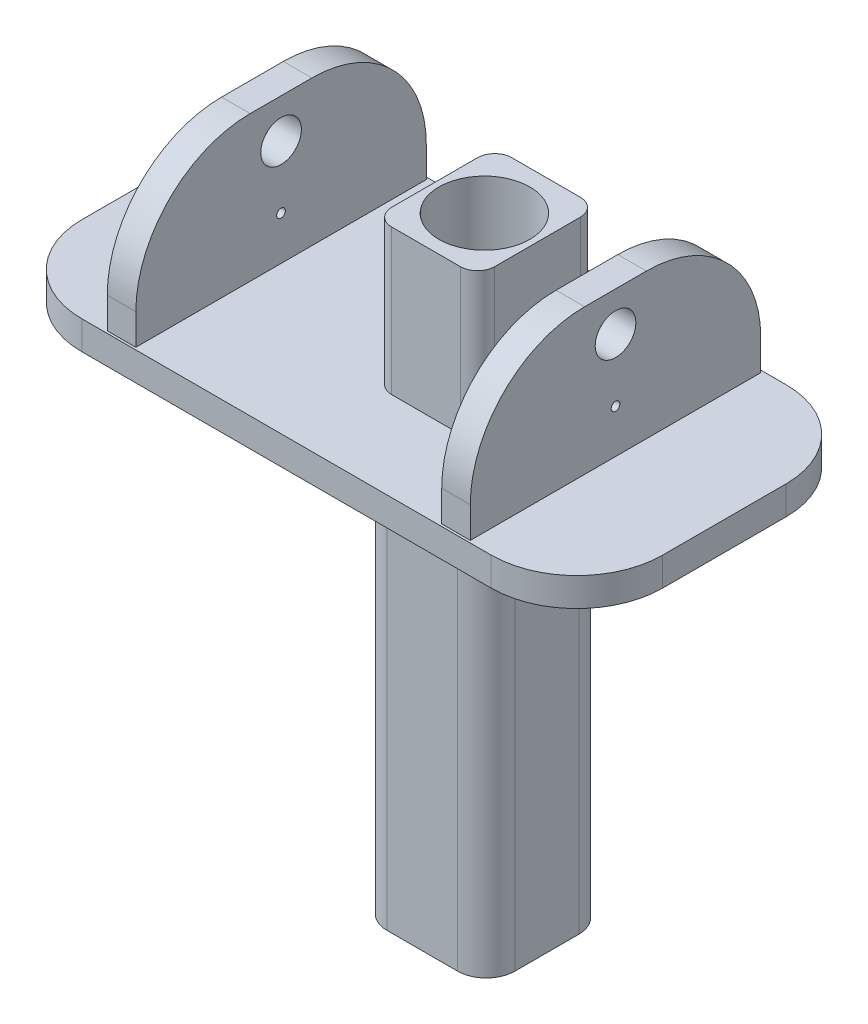
SolidWorks part; units mm, degrees
ref_plane "Front Plane" through (0, 0, 0) normal (0, 0, 1) x (1, 0, 0)
ref_plane "Top Plane" through (0, 0, 0) normal (0, 1, 0) x (1, 0, 0)
ref_plane "Right Plane" through (0, 0, 0) normal (1, 0, 0) x (0, 0, -1)
sketch "Sketch2" plane through (0, 0, 0) normal (0, 1, 0) x (1, 0, 0)
  line L1 (0, 0) -> (101.6, 0)
  line L2 (0, 0) -> (0, -101.6)
  line L3 (0, -101.6) -> (101.6, -101.6)
  line L4 (101.6, 0) -> (101.6, -101.6)
  dimension "D1" = 101.6
  dimension "D2" = 101.6
extrude "Boss-Extrude2" add sketch "Sketch2" along normal blind 5
sketch "Sketch3" plane through (0, 5, 0) normal (0, 1, 0) x (1, 0, 0)
  line L0 (0, 0) -> (0, -101.6) construction
  line L1 (19.05, -25.4) -> (24.05, -25.4)
  line L2 (19.05, -25.4) -> (19.05, -76.2)
  line L3 (19.05, -76.2) -> (24.05, -76.2)
  line L4 (24.05, -25.4) -> (24.05, -76.2)
  line L5 (0, -101.6) -> (101.6, -101.6) construction
  dimension "D1" = 5
  dimension "D2" = 19.05
  dimension "D3" = 50.8
  dimension "D4" = 25.4
extrude "Boss-Extrude3" add sketch "Sketch3" along normal blind 25.4
sketch "Sketch4" plane through (0, 5, 0) normal (0, 1, 0) x (1, 0, 0)
  line L0 (101.6, -101.6) -> (101.6, 0) construction
  line L1 (77.55, -25.4) -> (82.55, -25.4)
  line L2 (77.55, -25.4) -> (77.55, -76.2)
  line L3 (77.55, -76.2) -> (82.55, -76.2)
  line L4 (82.55, -25.4) -> (82.55, -76.2)
  line L5 (0, -101.6) -> (101.6, -101.6) construction
  dimension "D1" = 5
  dimension "D2" = 19.05
  dimension "D3" = 50.8
  dimension "D4" = 25.4
extrude "Boss-Extrude4" add sketch "Sketch4" along normal blind 25.4
sketch "Sketch8" plane through (19.05, 0, 0) normal (-1, 0, 0) x (0, 0, 1)
  line L0 (76.2, 30.4) -> (76.2, 5) construction
  line L1 (25.4, 5) -> (76.2, 5) construction
  circle A0 centre (50.8, 23.542) radius 3.556
  dimension "D1" = 25.4
  dimension "D2" = 18.542
extrude "Cut-Extrude1" cut sketch "Sketch8" against normal through all
sketch "Sketch9" plane through (82.55, 0, 0) normal (1, 0, 0) x (0, 0, -1)
  line L0 (-76.2, 30.4) -> (-76.2, 5) construction
  line L1 (-76.2, 5) -> (-25.4, 5) construction
  circle A0 centre (-50.8, 12.62) radius 0.762
  dimension "D1" = 25.4
  dimension "D2" = 7.62
extrude "Cut-Extrude2" cut sketch "Sketch9" against normal up to next
sketch "Sketch11" plane through (0, 5, 0) normal (0, 1, 0) x (1, 0, 0)
  line L0 (24.05, -76.2) -> (24.05, -25.4) construction
  line L1 (0, -101.6) -> (101.6, -101.6) construction
  circle A0 centre (59.61, -50.8) radius 7.9502
  dimension "D1" = 35.56
  dimension "D2" = 50.8
extrude "Cut-Extrude3" cut sketch "Sketch11" against normal through all
sketch "Sketch18" plane through (19.05, 0, 0) normal (-1, 0, 0) x (0, 0, 1)
  line L0 (0, 5) -> (101.6, 5) construction
  line L1 (25.4, 30.4) -> (25.4, 5) construction
  circle A0 centre (50.8, 12.62) radius 0.762
  dimension "D1" = 7.62
  dimension "D2" = 25.4
extrude "Cut-Extrude5" cut sketch "Sketch18" against normal up to next
sketch "Sketch19" plane through (0, 0, 0) normal (0, -1, 0) x (1, 0, 0)
  line L1 (48.1494, 61.3607) -> (70.4999, 61.3607)
  line L2 (48.1494, 61.3607) -> (48.1494, 40.1623)
  line L3 (48.1494, 40.1623) -> (70.4999, 40.1623)
  line L4 (70.4999, 61.3607) -> (70.4999, 40.1623)
extrude "Boss-Extrude5" add sketch "Sketch19" along normal blind 76.2
sketch "Sketch22" plane through (0, 0, 0) normal (0, 1, 0) x (1, 0, 0)
  circle A0 centre (59.61, -50.8) radius 7.94
extrude "Cut-Extrude7" cut sketch "Sketch22" against normal blind 72.2
sketch "Sketch23" plane through (0, -76.2, 0) normal (0, -1, 0) x (1, 0, 0)
  circle A0 centre (59.61, 50.8) radius 4.95
extrude "Cut-Extrude8" cut sketch "Sketch23" against normal through all
sketch "Sketch24" plane through (0, 5, 0) normal (0, 1, 0) x (1, 0, 0)
  line L0 (101.6, -101.6) -> (101.6, 0) construction
  line L1 (0, 0) -> (101.6, 0)
  line L2 (0, 0) -> (0, -25)
  line L3 (0, -25) -> (101.6, -25)
  line L4 (101.6, 0) -> (101.6, -25)
extrude "Cut-Extrude9" cut sketch "Sketch24" against normal through all
sketch "Sketch25" plane through (0, 5, 0) normal (0, 1, 0) x (1, 0, 0)
  line L0 (101.6, -101.6) -> (101.6, -25) construction
  line L1 (0, -101.6) -> (101.6, -101.6)
  line L2 (0, -101.6) -> (0, -76.6)
  line L3 (0, -76.6) -> (101.6, -76.6)
  line L4 (101.6, -101.6) -> (101.6, -76.6)
extrude "Cut-Extrude10" cut sketch "Sketch25" against normal through all
fillet "Fillet1" radius 20 1 edges at (21.55, 30.4, 76.2)
fillet "Fillet2" radius 20 1 edges at (21.55, 30.4, 25.4)
fillet "Fillet3" radius 20 1 edges at (80.05, 30.4, 25.4)
fillet "Fillet4" radius 20 1 edges at (80.05, 30.4, 76.2)
fillet "Fillet5" radius 15 1 edges at (101.6, 2.5, 76.6)
fillet "Fillet6" radius 15 1 edges at (101.6, 2.5, 25)
fillet "Fillet7" radius 15 1 edges at (0, 2.5, 25)
fillet "Fillet8" radius 15 1 edges at (0, 2.5, 76.6)
fillet "Fillet9" radius 5 1 edges at (70.4999, -38.1, 61.3607)
fillet "Fillet10" radius 5 1 edges at (70.4999, -38.1, 40.1623)
fillet "Fillet11" radius 5 1 edges at (48.1494, -38.1, 61.3607)
fillet "Fillet12" radius 5 1 edges at (48.1494, -38.1, 40.1623)
sketch "Sketch35" plane through (0, 5, 0) normal (0, 1, 0) x (1, 0, 0)
  line L1 (50.61, -40) -> (68.61, -40)
  line L2 (50.61, -40) -> (50.61, -61)
  line L3 (50.61, -61) -> (68.61, -61)
  line L4 (68.61, -40) -> (68.61, -61)
extrude "Boss-Extrude7" add sketch "Sketch35" along normal blind 25.4
sketch "Sketch36" plane through (0, 30.4, 0) normal (0, 1, 0) x (1, 0, 0)
  circle A0 centre (59.61, -50.8) radius 7.95
extrude "Cut-Extrude12" cut sketch "Sketch36" against normal up to next
fillet "Fillet18" radius 3 1 edges at (50.61, 17.7, 61)
fillet "Fillet19" radius 3 1 edges at (68.61, 17.7, 61)
fillet "Fillet20" radius 3 1 edges at (68.61, 17.7, 40)
fillet "Fillet21" radius 3 1 edges at (50.61, 17.7, 40)
